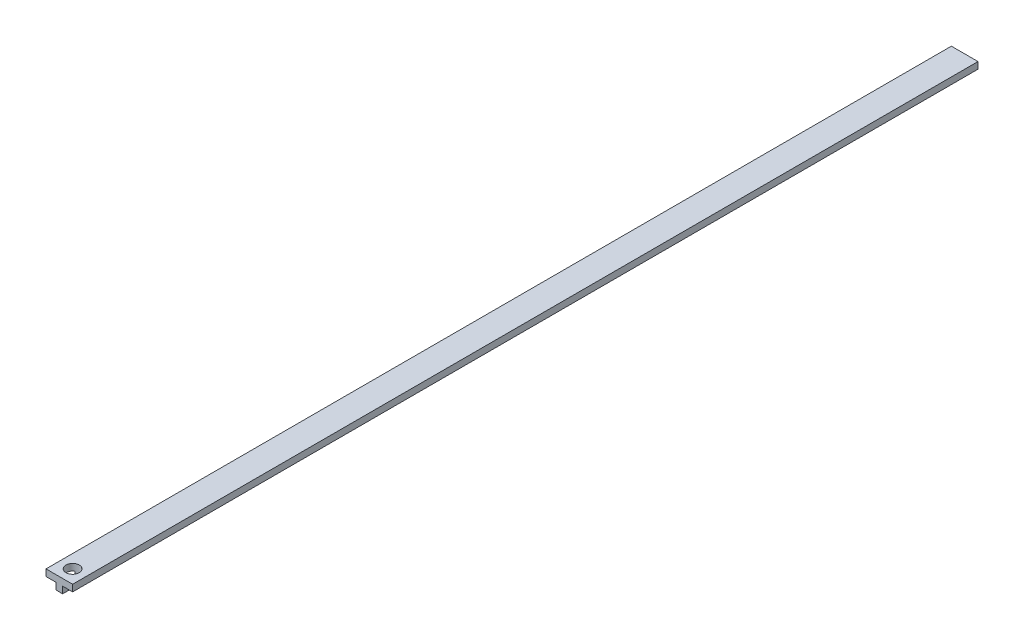
SolidWorks part; units mm, degrees
ref_plane "Front Plane" through (0, 0, 0) normal (0, 0, 1) x (1, 0, 0)
ref_plane "Top Plane" through (0, 0, 0) normal (0, 1, 0) x (1, 0, 0)
ref_plane "Right Plane" through (0, 0, 0) normal (1, 0, 0) x (0, 0, -1)
sketch "Sketch1" plane through (0, 0, 0) normal (0, 0, 1) x (1, 0, 0)
  line L0 (-6.35, 0) -> (6.35, 0) construction
  line L1 (0, -3.175) -> (0, 3.175) construction
  line L5 (-6.35, 3.175) -> (6.35, 3.175) construction
  line L7 (-6.35, 3.175) -> (-6.35, 0) construction
  line L8 (6.35, 0) -> (6.35, 3.175) construction
  line L9 (6.35, 0) -> (-6.35, 0) construction
  line L12 (-1.5875, 0) -> (-1.5875, -3.175) construction
  line L13 (-1.5875, -3.175) -> (1.5875, -3.175) construction
  line L14 (1.5875, -3.175) -> (1.5875, 0) construction
  point P0 (0, 0)
  point P4 (0, 0)
  point P9 (0, 0)
  point P15 (0, 0)
  point P16 (0, -3.175)
  point P22 (0, 3.175)
  point P26 (0, 0)
  dimension "Outside Height" = 6.35
  dimension "Wall Thickness" = 3.175
  dimension "D1" = 3.175
  dimension "Outside Width" = 12.7
sketch "Sketch2" plane through (0, 0, 0) normal (1, 0, 0) x (0, 0, -1)
  line L0 (215.9, 3.175) -> (-215.9, 3.175) construction
  point P3 (-201.295, 3.175)
  point P5 (201.295, 3.175)
  point P7 (0, 3.175)
  dimension "D1" = 14.605
  dimension "D2" = 14.605
  dimension "Length" = 431.8
sketch "Sketch3" plane through (0, 0, 0) normal (0, 0, 1) x (1, 0, 0)
  line L0 (-6.35, 3.175) -> (6.35, 3.175)
  line L10 (6.35, 3.175) -> (6.35, 0)
  line L11 (6.35, 0) -> (1.5875, 0)
  line L12 (1.5875, 0) -> (1.5875, -3.175)
  line L13 (1.5875, -3.175) -> (-1.5875, -3.175)
  line L14 (-1.5875, -3.175) -> (-1.5875, 0)
  line L15 (-1.5875, 0) -> (-6.35, 0)
  line L16 (-6.35, 0) -> (-6.35, 3.175)
extrude "Boss-Extrude1" add sketch "Sketch3" along normal mid plane 431.8
sketch "Sketch4" plane through (0, 3.175, 0) normal (0, 1, 0) x (1, 0, 0)
  line L0 (6.35, -215.9) -> (-6.35, -215.9) construction
  circle A0 centre (0, -209.55) radius 3.175
  dimension "D1" = 6.35
  dimension "D2" = 6.35
extrude "Cut-Extrude1" cut sketch "Sketch4" against normal through all
equation "\"D1@Boss-Extrude1\" = \"Length@Sketch2\""
equation "\"D1@Sketch2\" = \"Outside Width@Sketch1\" * 1.15"
equation "\"D2@Sketch2\"=\"D1@Sketch2\""
equation "\"D1@Sketch1\"=\"Wall Thickness@Sketch1\""
